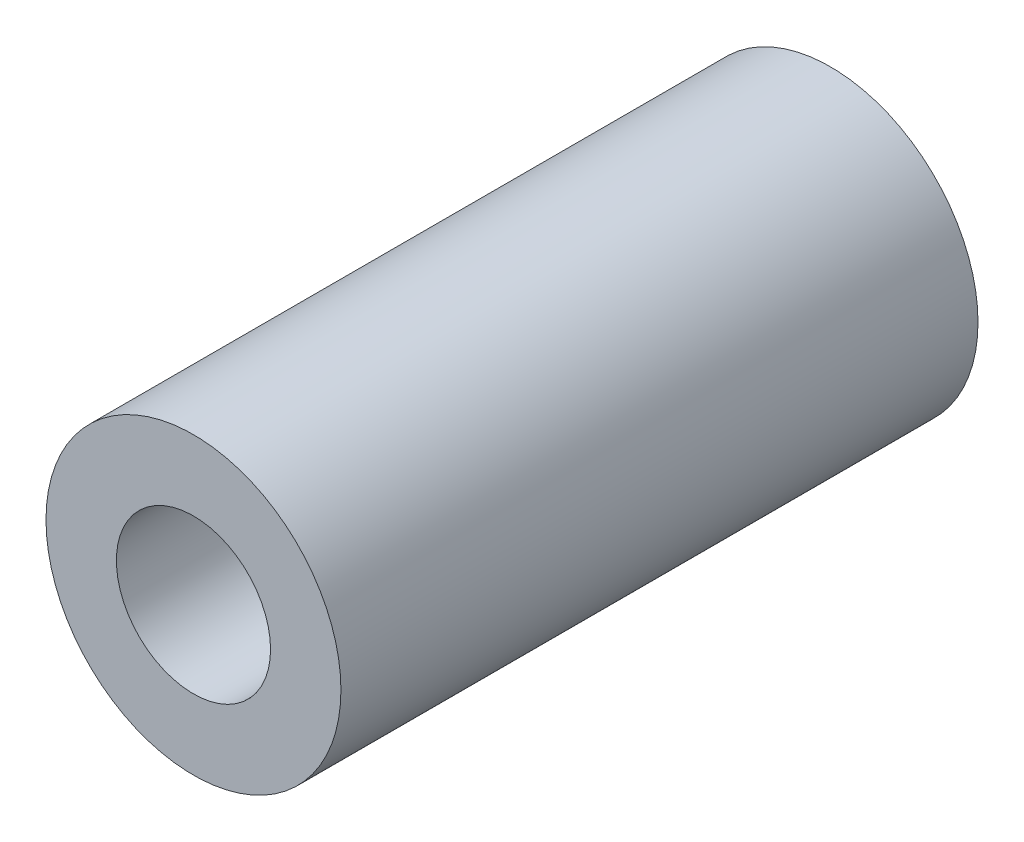
SolidWorks part; units mm, degrees
ref_plane "Front Plane" through (0, 0, 0) normal (0, 0, 1) x (1, 0, 0)
ref_plane "Top Plane" through (0, 0, 0) normal (0, 1, 0) x (1, 0, 0)
ref_plane "Right Plane" through (0, 0, 0) normal (1, 0, 0) x (0, 0, -1)
sketch "Sketch1" plane through (0, 0, 0) normal (0, 0, 1) x (1, 0, 0)
  circle A0 centre (0, 0) radius 4.7625
  circle A1 centre (0, 0) radius 2.4892
  dimension "D1" = 9.525
  dimension "D2" = 4.9784
extrude "Boss-Extrude1" add sketch "Sketch1" along normal mid plane 20.574
